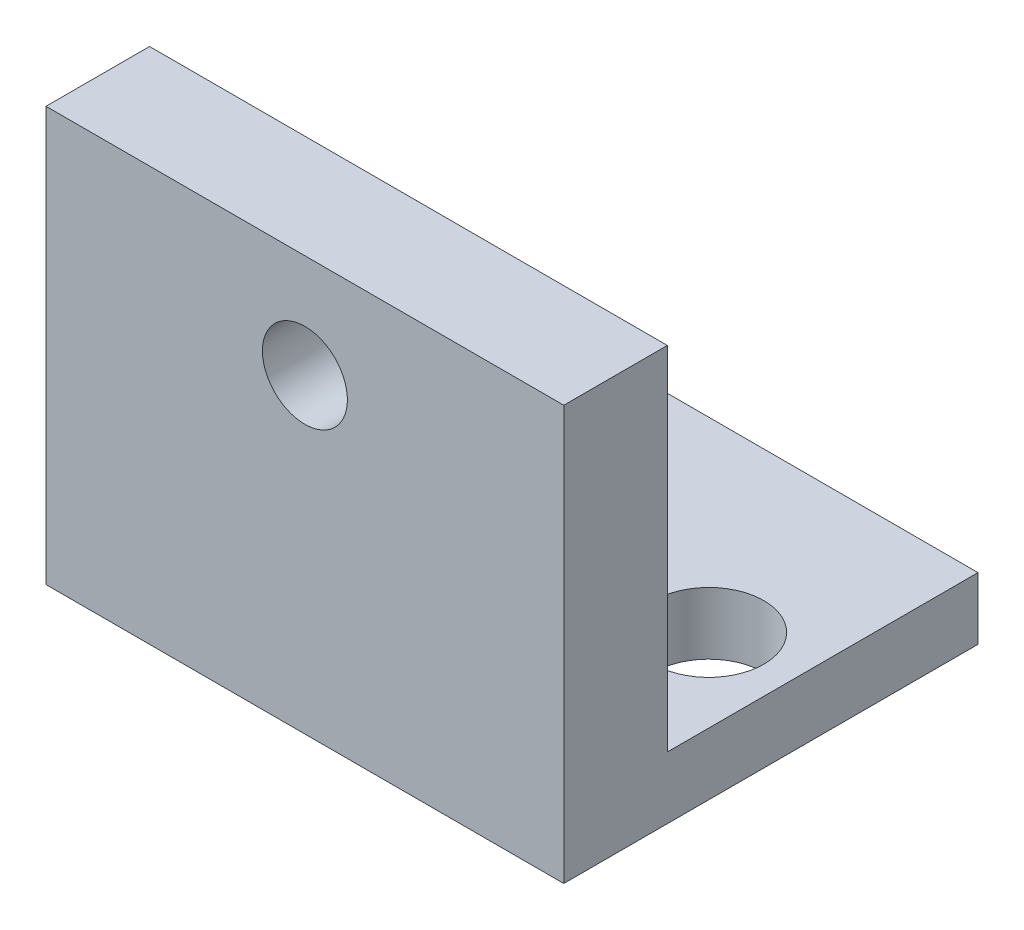
SolidWorks part; units mm, degrees
material "1023 Carbon Steel Sheet (SS)"
ref_plane "Front Plane" through (0, 0, 0) normal (0, 0, 1) x (1, 0, 0)
ref_plane "Top Plane" through (0, 0, 0) normal (0, 1, 0) x (1, 0, 0)
ref_plane "Right Plane" through (0, 0, 0) normal (1, 0, 0) x (0, 0, -1)
sketch "Sketch2" plane through (0, 0, 0) normal (1, 0, 0) x (0, 0, -1)
  line L0 (0, 0) -> (25.4, 0)
  line L1 (25.4, 0) -> (25.4, 6.35)
  line L2 (25.4, 6.35) -> (6.35, 6.35)
  line L3 (6.35, 6.35) -> (6.35, 25.4)
  line L4 (6.35, 25.4) -> (0, 25.4)
  line L5 (0, 25.4) -> (0, 0)
  dimension "D1" = 6.35
  dimension "D2" = 6.35
  dimension "D3" = 25.4
  dimension "D4" = 25.4
extrude "Boss-Extrude1" add sketch "Sketch2" along normal blind 31.75
sketch "Sketch3" plane through (0, 0, -6.35) normal (0, 0, -1) x (-1, 0, 0)
  line L1 (0, 6.35) -> (0, 25.4) construction
  line L2 (-31.75, 0) -> (0, 0) construction
  circle A0 centre (-15.875, 19.05) radius 2.6035
  dimension "D6" = 5.207
  dimension "D5" = 19.05
  dimension "D7" = 15.875
extrude "Cut-Extrude1" cut sketch "Sketch3" against normal through all
sketch "Sketch4" plane through (0, 6.35, 0) normal (0, 1, 0) x (1, 0, 0)
  line L0 (0, 25.4) -> (0, 6.35) construction
  line L1 (31.75, 25.4) -> (31.75, 6.35) construction
  line L2 (31.75, 25.4) -> (0, 25.4) construction
  circle A1 centre (5.08, 17.78) radius 3.3782
  circle A2 centre (26.67, 13.97) radius 3.3782
  dimension "D1" = 5.08
  dimension "D3" = 5.08
  dimension "D4" = 6.7564
  dimension "D2" = 6.7564
  dimension "D5" = 7.62
  dimension "D6" = 11.43
extrude "Cut-Extrude2" cut sketch "Sketch4" against normal through all
sketch "Sketch5" plane through (0, 6.35, 0) normal (0, 1, 0) x (1, 0, 0)
  line L1 (0, 25.4) -> (31.75, 25.4)
  line L2 (0, 25.4) -> (0, 6.35)
  line L3 (0, 6.35) -> (31.75, 6.35)
  line L4 (31.75, 25.4) -> (31.75, 6.35)
extrude "Cut-Extrude3" cut sketch "Sketch5" against normal blind 2.54
